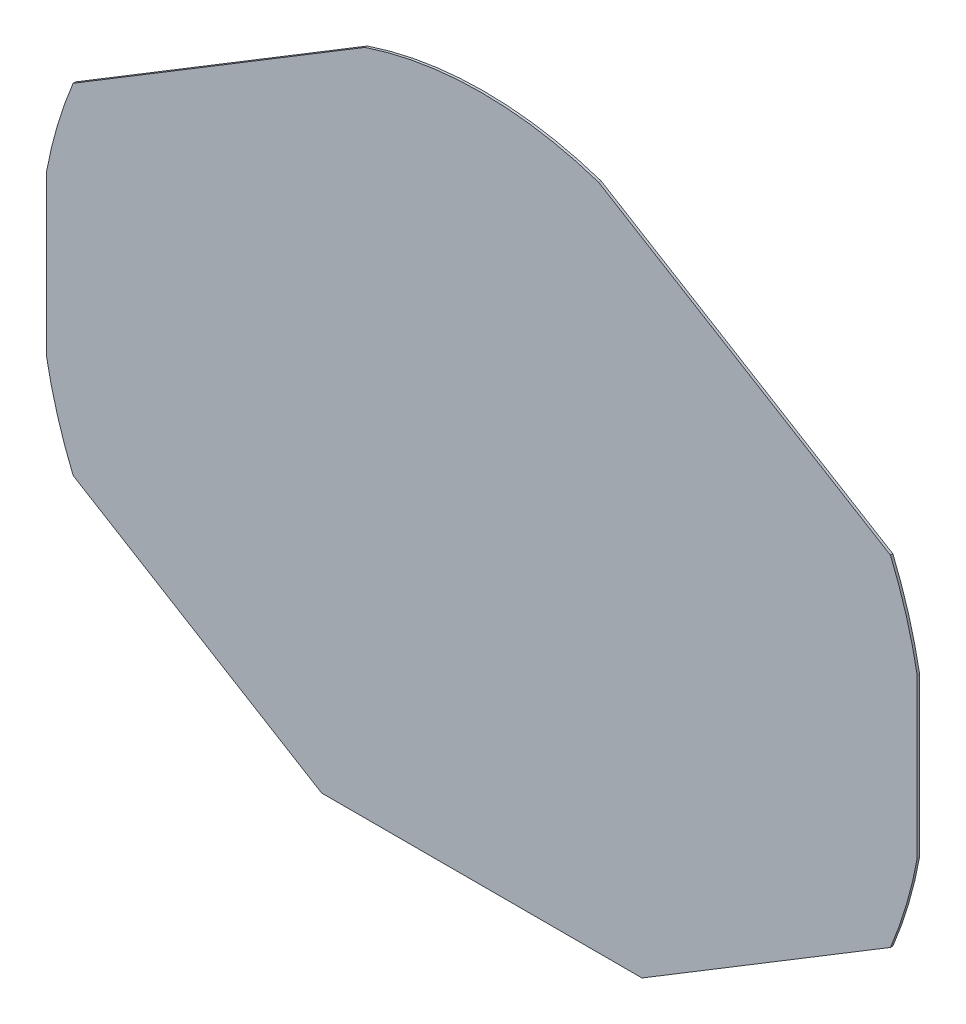
SolidWorks part; units mm, degrees
material "Polyol polyéther"
ref_plane "Plan de face" through (0, 0, 0) normal (0, 0, 1) x (1, 0, 0)
ref_plane "Plan de dessus" through (0, 0, 0) normal (0, 1, 0) x (1, 0, 0)
ref_plane "Plan de droite" through (0, 0, 0) normal (1, 0, 0) x (0, 0, -1)
sketch "Esquisse1" plane through (0, 0, 0) normal (0, 0, 1) x (1, 0, 0)
  line L0 (9.1, 1.6591) -> (9.1, -1.6591)
  line L1 (0, 0) -> (0, -5.4382) construction
  line L2 (0, 0) -> (11.9494, 0) construction
  line L3 (2.4413, 7.25) -> (8.5417, 3.55)
  line L4 (-9.1, 1.6591) -> (-9.1, -1.6591)
  line L5 (-2.4413, 7.25) -> (-8.5417, 3.55)
  line L6 (-3.3481, -6.7) -> (3.3481, -6.7)
  line L7 (0, 0) -> (0, -6.7) construction
  line L8 (-3.3481, -6.7) -> (-8.5417, -3.55)
  line L9 (3.3481, -6.7) -> (8.5417, -3.55)
  arc A0 (2.4413, 7.25) -> (-2.4413, 7.25) centre (0, 0) ccw
  arc A1 (9.1, 1.6591) -> (8.5417, 3.55) centre (0, 0) ccw
  arc A2 (-9.1, 1.6591) -> (-8.5417, 3.55) centre (0, 0) cw
  arc A3 (-9.1, -1.6591) -> (-8.5417, -3.55) centre (0, 0) ccw
  arc A4 (9.1, -1.6591) -> (8.5417, -3.55) centre (0, 0) cw
  point P1 (-9.1, 0)
  point P5 (2.4413, 7.25)
  point P7 (8.5417, 3.55)
  point P10 (-2.4413, -7.25)
  point P13 (-8.5417, 3.55)
  point P14 (-2.4413, 7.25)
  point P19 (9.1, 0)
  point P20 (-8.5417, -3.55)
  point P21 (8.5417, -3.55)
  point P22 (2.4413, -7.25)
  point P26 (0, 0)
  dimension "D1" = 15.3
  dimension "D5" = 9.25
  dimension "D2" = 18.2
  dimension "D3" = 7.1
  dimension "D4" = 7.25
  dimension "D6" = 6.7
  dimension "D7" = 31.238
extrude "Boss.-Extru.1" add sketch "Esquisse1" along normal blind 0.05
